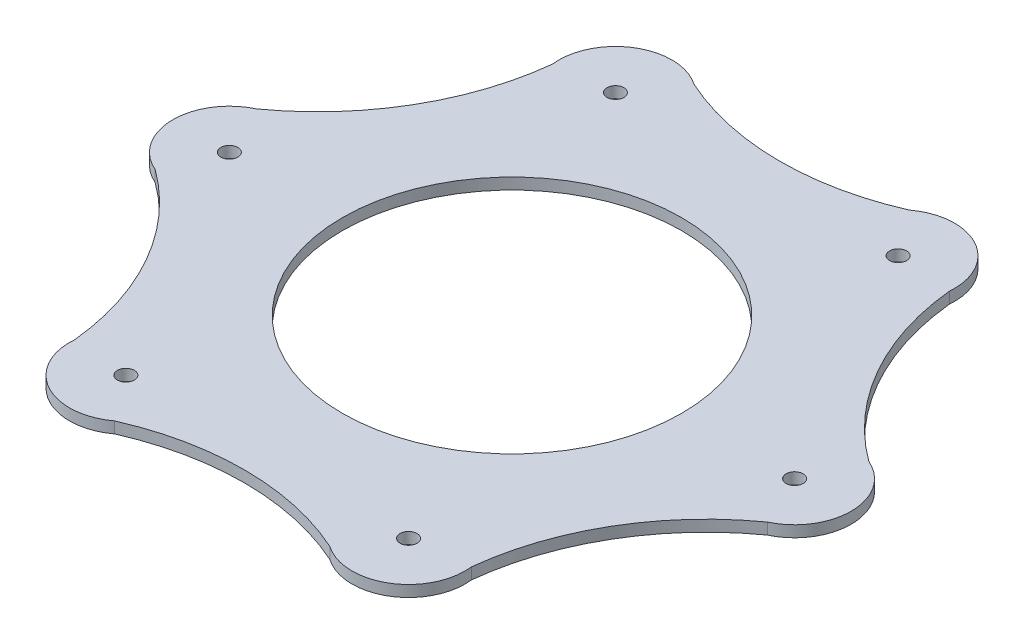
SolidWorks part; units mm, degrees
material "1060 Alloy"
ref_plane "Front Plane" through (0, 0, 0) normal (0, 0, 1) x (1, 0, 0)
ref_plane "Top Plane" through (0, 0, 0) normal (0, 1, 0) x (1, 0, 0)
ref_plane "Right Plane" through (0, 0, 0) normal (1, 0, 0) x (0, 0, -1)
sketch "Sketch1" plane through (0, 0, 0) normal (0, 1, 0) x (1, 0, 0)
  line L0 (101.2154, 0) -> (-101.2154, 0) construction
  arc A0 (-34.9629, -42.4412) -> (-19.0052, -51.3051) centre (-25, -43.3013) ccw
  arc A1 (-19.0052, -51.3051) -> (19.2736, -51.4994) centre (-0.0829, -94.1878) cw
  arc A2 (19.2736, -51.4994) -> (34.929, -42.1115) centre (25, -43.3013) ccw
  arc A3 (34.929, -42.1115) -> (54.2366, -9.0582) centre (81.5276, -47.1656) cw
  arc A4 (54.2366, -9.0582) -> (53.9341, 9.1936) centre (50, 0) ccw
  arc A5 (53.9341, 9.1936) -> (34.9629, 42.4412) centre (81.6104, 47.0221) cw
  arc A6 (34.9629, 42.4412) -> (19.0052, 51.3051) centre (25, 43.3013) ccw
  arc A7 (19.0052, 51.3051) -> (-19.2736, 51.4994) centre (0.0829, 94.1878) cw
  arc A8 (-19.2736, 51.4994) -> (-34.929, 42.1115) centre (-25, 43.3013) ccw
  arc A9 (-34.929, 42.1115) -> (-54.2366, 9.0582) centre (-81.5276, 47.1656) cw
  arc A10 (-54.2366, 9.0582) -> (-53.9341, -9.1936) centre (-50, 0) ccw
  arc A11 (-53.9341, -9.1936) -> (-34.9629, -42.4412) centre (-81.6104, -47.0221) cw
  circle A12 centre (0, 0) radius 30
  circle A13 centre (50, 0) radius 1.5
  circle A14 centre (25, -43.3013) radius 1.5
  circle A15 centre (25, 43.3013) radius 1.5
  circle A16 centre (-25, -43.3013) radius 1.5
  circle A17 centre (-50, 0) radius 1.5
  circle A18 centre (-25, 43.3013) radius 1.5
  point P32 (0, 0)
  point P35 (0, 0)
  dimension "D1" = 60
  dimension "D2" = 10
  dimension "D3" = 3
  dimension "D4" = 50
extrude "Boss-Extrude1" add sketch "Sketch1" against normal blind 2
